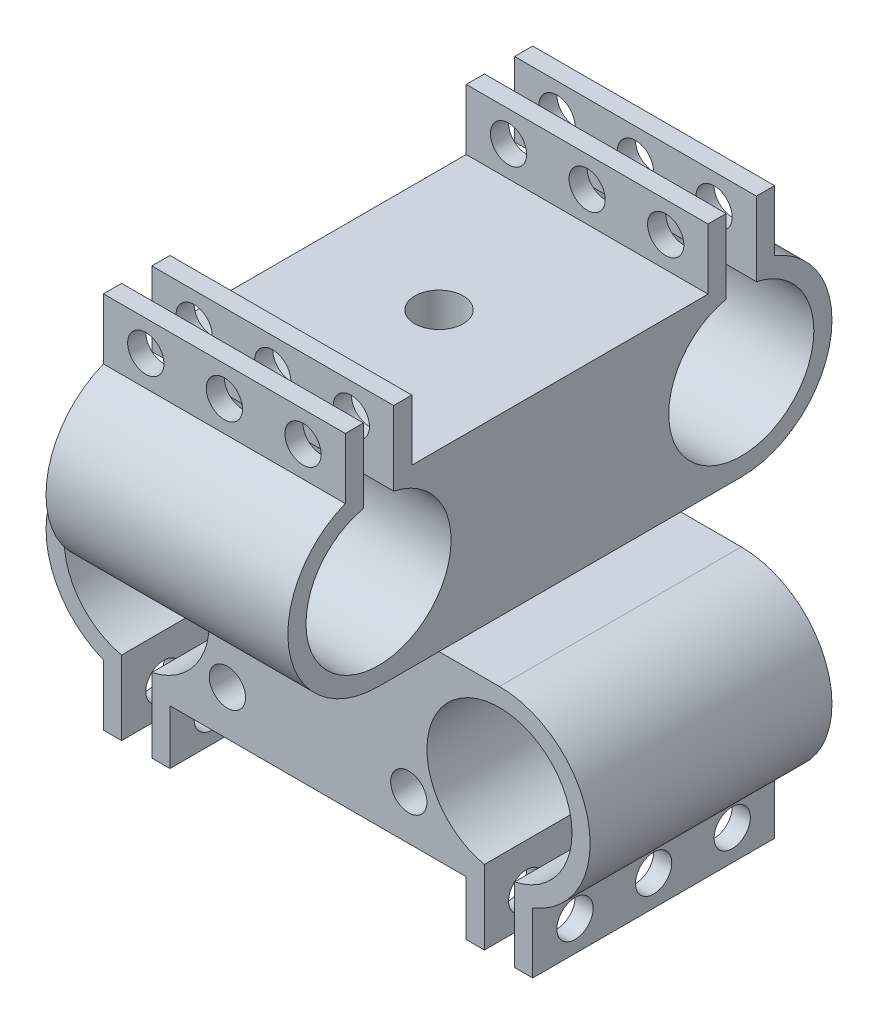
SolidWorks part; units mm, degrees
ref_plane "정면" through (0, 0, 0) normal (0, 0, 1) x (1, 0, 0)
ref_plane "윗면" through (0, 0, 0) normal (0, 1, 0) x (1, 0, 0)
ref_plane "우측면" through (0, 0, 0) normal (1, 0, 0) x (0, 0, -1)
sketch "스케치1" plane through (0, 0, 0) normal (1, 0, 0) x (0, 0, -1)
  line L0 (0, 7.5) -> (0, -7.5) construction
  line L1 (-12.25, 0) -> (12.25, 0) construction
  line L2 (-15, 0) -> (15, 0) construction
  line L3 (-17.75, 12) -> (-16.25, 12)
  line L4 (-17.75, 12) -> (-17.75, 5.3327)
  line L5 (-12.75, 0) -> (12.75, 0) construction
  line L6 (-12.25, 12) -> (-12.25, 5.3327)
  line L7 (-17.75, -0.0455) -> (-12.25, 0) construction
  line L8 (12.25, 12) -> (12.25, 0) construction
  line L9 (12.25, 12) -> (12.25, 5.3327)
  line L10 (17.75, 12) -> (17.75, 5.3327)
  line L11 (17.75, 12) -> (16.25, 12)
  line L12 (-13.75, 10.5) -> (-13.75, 5.8683)
  line L13 (13.75, 10.5) -> (13.75, 1.5) construction
  line L14 (-16.25, 10.5) -> (-16.25, 5.8683)
  line L15 (13.75, 12) -> (12.25, 12)
  line L16 (13.75, 10.5) -> (13.75, 5.8683)
  line L17 (-12.25, 6.9776) -> (12.25, 6.9776)
  line L18 (16.25, 10.5) -> (16.25, 5.8683)
  line L19 (16.25, 10.5) -> (16.25, 1.5) construction
  line L20 (-16.25, 10.5) -> (-16.25, 12)
  line L21 (-13.75, 10.5) -> (-13.75, 12)
  line L22 (13.75, 10.5) -> (13.75, 12)
  line L23 (16.25, 10.5) -> (16.25, 12)
  line L24 (-16.25, 10.5) -> (-13.75, 10.5) construction
  line L25 (-13.75, 12) -> (-12.25, 12)
  line L26 (-17.75, 12) -> (-12.25, 12) construction
  line L27 (16.25, 10.5) -> (13.75, 10.5) construction
  line L28 (17.75, 12) -> (12.25, 12) construction
  line L29 (-15, -7.5) -> (15, -7.5)
  line L30 (17.75, 12) -> (17.75, 0) construction
  line L31 (-17.75, 12) -> (-17.75, -0.0455) construction
  line L33 (-16.25, 10.5) -> (-16.25, 1.467) construction
  line L35 (-13.75, 10.5) -> (-13.75, 1.4876) construction
  line L36 (-12.25, 12) -> (-12.25, 0) construction
  line L37 (-16.25, 1.467) -> (-13.75, 1.4876) construction
  line L38 (16.25, 1.5) -> (13.75, 1.5) construction
  line L39 (17.75, 0) -> (12.25, 0) construction
  arc A0 (-16.25, 5.8683) -> (-13.75, 5.8683) centre (-15, 0) ccw
  arc A1 (16.25, 5.8683) -> (13.75, 5.8683) centre (15, 0) cw
  arc A2 (-16.25, 7.3951) -> (-13.75, 7.3951) centre (-15, 0) ccw
  arc A3 (16.25, 7.3951) -> (13.75, 7.3951) centre (15, 0) cw
  circle A4 centre (-15, 0) radius 6 construction
  circle A5 centre (-15, 0) radius 7.5 construction
  point P3 (0, 0)
  point P12 (-15, 6)
  dimension "D1" = 12
  dimension "D2" = 30
  dimension "D4" = 12
  dimension "D5" = 5.5
  dimension "D7" = 6.6673
  dimension "D3" = 1.5
  dimension "D6" = 1.5
extrude "보스-돌출1" add sketch "스케치1" along normal blind 20 contours L29 A3 L17 A2 | L4 A2 L6 A0 | L6 A2 L12 A0 | L14 A2 L4 A0 | A2 L14 L20 L3 L4 | A2 L6 L25 L21 L12 | A3 L10 A1 L9 | A3 L18 A1 L10 | L18 A3 L10 L11 L23 | L9 A3 L16 L22 L15 | A3 L9 A1 L16
sketch "스케치2" plane through (0, 0, 17.75) normal (0, 0, 1) x (1, 0, 0)
  line L0 (0, 9.4888) -> (20, 9.4888) construction
  line L1 (10, 12) -> (10, 6.9776) construction
  line L2 (3.5, 12) -> (3.5, 6.9776) construction
  line L3 (16.5, 12) -> (16.5, 6.9776) construction
  line L4 (0, 12) -> (0, 6.9776)
  line L5 (0, 6.9776) -> (20, 6.9776)
  line L6 (20, 6.9776) -> (20, 12)
  line L7 (20, 12) -> (0, 12)
  line L8 (0, 12) -> (0, 6.9776)
  line L9 (0, 6.9776) -> (20, 6.9776)
  line L10 (20, 6.9776) -> (20, 12)
  line L11 (20, 12) -> (0, 12)
  circle A0 centre (3.5, 9.4888) radius 1.5
  circle A1 centre (16.5, 9.4888) radius 1.5
  circle A2 centre (10, 9.4888) radius 1.5
  point P14 (3.5, 9.4888)
  point P17 (16.5, 9.4888)
  dimension "D3" = 3
  dimension "D2" = 6.5
  dimension "D1" = 0
extrude "컷-돌출1" cut sketch "스케치2" against normal through all contours A0 | A2 | A1
sketch "스케치5" plane through (0, 0, 0) normal (0, 0, 1) x (1, 0, 0)
  line L0 (-72.0207, -10.4098) -> (-72.0207, -25.4098) construction
  line L1 (-84.2707, -17.9098) -> (-59.7707, -17.9098) construction
  line L2 (-87.0207, -17.9098) -> (-57.0207, -17.9098) construction
  line L3 (-89.7707, -5.9098) -> (-88.2707, -5.9098)
  line L4 (-89.7707, -5.9098) -> (-89.7707, -12.5771)
  line L5 (-84.7707, -17.9098) -> (-59.2707, -17.9098) construction
  line L6 (-84.2707, -5.9098) -> (-84.2707, -12.5771)
  line L7 (-59.7707, -5.9098) -> (-59.7707, -12.5771)
  line L8 (-54.2707, -5.9098) -> (-54.2707, -12.5771)
  line L9 (-54.2707, -5.9098) -> (-55.7707, -5.9098)
  line L10 (-85.7707, -7.4098) -> (-85.7707, -12.0415)
  line L11 (-88.2707, -7.4098) -> (-88.2707, -12.0415)
  line L12 (-58.2707, -5.9098) -> (-59.7707, -5.9098)
  line L13 (-58.2707, -7.4098) -> (-58.2707, -12.0415)
  line L14 (-84.2707, -10.9322) -> (-59.7707, -10.9322)
  line L15 (-55.7707, -7.4098) -> (-55.7707, -12.0415)
  line L16 (-88.2707, -7.4098) -> (-88.2707, -5.9098)
  line L17 (-85.7707, -7.4098) -> (-85.7707, -5.9098)
  line L18 (-58.2707, -7.4098) -> (-58.2707, -5.9098)
  line L19 (-55.7707, -7.4098) -> (-55.7707, -5.9098)
  line L20 (-85.7707, -5.9098) -> (-84.2707, -5.9098)
  line L21 (-87.0207, -25.4098) -> (-57.0207, -25.4098)
  line L22 (20, -7.5) -> (0, -7.5) construction
  line L23 (25, -7.5) -> (-5, -7.5)
  line L24 (25, -7.5) -> (25, -22.5) construction
  line L25 (25, -22.5) -> (-5, -22.5)
  line L26 (-5, -7.5) -> (-5, -22.5) construction
  line L27 (20, -7.5) -> (0, -7.5)
  line L28 (-2.25, -20.3327) -> (-2.25, -27.0027)
  line L29 (-7.75, -20.3327) -> (-6.25, -20.3327)
  line L30 (-7.75, -20.3327) -> (-7.75, -27.0027)
  line L31 (-7.75, -27.0027) -> (-6.25, -27.0027)
  line L32 (-6.25, -20.3327) -> (-6.25, -27.0027)
  line L33 (-2.25, -20.3327) -> (-3.75, -20.3327)
  line L34 (-3.75, -20.3327) -> (-3.75, -27.0027)
  line L35 (-2.25, -27.0027) -> (-3.75, -27.0027)
  line L36 (10, -7.5) -> (10, -22.5) construction
  line L37 (22.25, -20.3327) -> (23.75, -20.3327)
  line L38 (27.75, -20.3327) -> (26.25, -20.3327)
  line L39 (27.75, -20.3327) -> (27.75, -27.0027)
  line L40 (22.25, -20.3327) -> (22.25, -27.0027)
  line L41 (23.75, -20.3327) -> (23.75, -27.0027)
  line L42 (26.25, -20.3327) -> (26.25, -27.0027)
  line L43 (22.25, -27.0027) -> (23.75, -27.0027)
  line L44 (27.75, -27.0027) -> (26.25, -27.0027)
  arc A0 (-88.2707, -12.0415) -> (-85.7707, -12.0415) centre (-87.0207, -17.9098) ccw
  arc A1 (-55.7707, -12.0415) -> (-58.2707, -12.0415) centre (-57.0207, -17.9098) cw
  arc A2 (-88.2707, -10.5147) -> (-85.7707, -10.5147) centre (-87.0207, -17.9098) ccw
  arc A3 (-55.7707, -10.5147) -> (-58.2707, -10.5147) centre (-57.0207, -17.9098) cw
  circle A4 centre (-5, -15) radius 7.5
  circle A5 centre (25, -15) radius 7.5
  circle A6 centre (-5, -15) radius 6
  circle A7 centre (25, -15) radius 6
  point P2 (-72.0207, -17.9098)
  point P11 (-87.0207, -11.9098)
  point P44 (10, -7.5)
  point P47 (10, -7.5)
  point P72 (-7.75, -21.9776)
  point P73 (-6.25, -19.1657)
  point P74 (-3.75, -22.3951)
  point P75 (-2.25, -21.4476)
  point P76 (22.25, -21.9776)
  point P77 (23.75, -22.3951)
  point P78 (26.25, -22.3951)
  point P79 (27.75, -21.9776)
  dimension "D4" = 6
  dimension "D5" = 7.5
  dimension "D10" = 12
  dimension "D1" = 24.5
  dimension "D2" = 30
  dimension "D3" = 30
  dimension "D6" = 6.6673
  dimension "D7" = 1.5
  dimension "D8" = 30
  dimension "D9" = 15
  dimension "D11" = 1.5
  dimension "D12" = 6.67
  dimension "D13" = 2.5
  dimension "D14" = 2.5
extrude "보스-돌출2" add sketch "스케치5" along normal mid plane 20 contours A7 L39 A5 L40 | A7 L40 A5 L41 | A7 L42 A5 L39 | A5 L42 L44 L39 | A5 L40 L25 L41 | L40 L43 L41 L25 | A5 L23 A4 L28 L25 L40 | A6 L28 A4 L30 | A6 L30 A4 L32 | A4 L30 L31 L32 | A4 L34 L25 L28 | L35 L28 L25 L34 | A6 L34 A4 L28
sketch "스케치6" plane through (27.75, 0, 0) normal (1, 0, 0) x (0, 0, -1)
  line L0 (0, 0) -> (0, -27.0027) construction
  line L1 (-10, -24.4902) -> (10, -24.4902) construction
  line L4 (10, -27.0027) -> (10, -21.9776)
  line L5 (10, -21.9776) -> (-10, -21.9776)
  line L6 (-10, -21.9776) -> (-10, -27.0027)
  line L7 (-10, -27.0027) -> (10, -27.0027)
  line L8 (10, -27.0027) -> (10, -21.9776)
  line L9 (10, -21.9776) -> (-10, -21.9776)
  line L10 (-10, -21.9776) -> (-10, -27.0027)
  line L11 (-10, -27.0027) -> (10, -27.0027)
  circle A0 centre (-6.5, -24.4902) radius 1.5
  circle A1 centre (6.5, -24.4902) radius 1.5
  circle A2 centre (0, -24.4902) radius 1.5
  dimension "D3" = 3
  dimension "D2" = 6.5
  dimension "D1" = 0
extrude "컷-돌출2" cut sketch "스케치6" against normal through all contours A0 | A2 | A1
sketch "스케치7" plane through (0, 6.9776, 0) normal (0, 1, 0) x (1, 0, 0)
  line L0 (0, 0) -> (20, 0) construction
  line L1 (20, -12.25) -> (20, 12.25) construction
  line L2 (10, 12.25) -> (10, -12.25) construction
  line L3 (20, 12.25) -> (0, 12.25) construction
  line L4 (20, -12.25) -> (0, -12.25) construction
  circle A0 centre (10, 0) radius 2
  dimension "D1" = 4
extrude "컷-돌출3" cut sketch "스케치7" against normal through all
sketch "스케치8" plane through (0, -22.5, 0) normal (0, -1, 0) x (1, 0, 0)
  circle A0 centre (10, 0) radius 6
  circle A1 centre (10, 0) radius 8
  dimension "D1" = 12
  dimension "D2" = 16
extrude "컷-돌출4" cut sketch "스케치8" against normal blind 10 contours A1
sketch "스케치9" plane through (0, 0, 10) normal (0, 0, 1) x (1, 0, 0)
  line L0 (10, -7.5) -> (10, -22.5) construction
  line L1 (20, -7.5) -> (0, -7.5) construction
  line L2 (22.25, -22.5) -> (-2.25, -22.5) construction
  circle A0 centre (17.5, -18.8) radius 1.5
  circle A1 centre (2.5, -18.8) radius 1.5
  dimension "D1" = 3
  dimension "D2" = 15
  dimension "D3" = 3.7
extrude "컷-돌출5" cut sketch "스케치9" against normal through all
